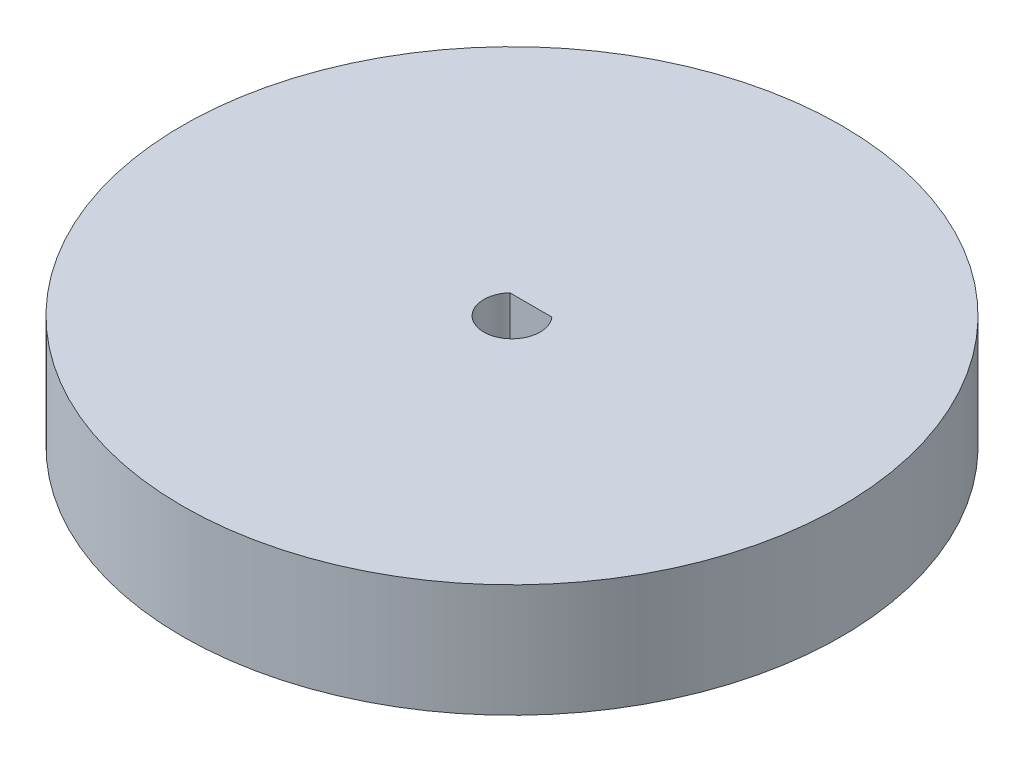
SolidWorks part; units mm, degrees
material "6063-T4"
ref_plane "Front Plane" through (0, 0, 0) normal (0, 0, 1) x (1, 0, 0)
ref_plane "Top Plane" through (0, 0, 0) normal (0, 1, 0) x (1, 0, 0)
ref_plane "Right Plane" through (0, 0, 0) normal (1, 0, 0) x (0, 0, -1)
sketch "Sketch1" plane through (0, 0, 0) normal (0, 1, 0) x (1, 0, 0)
  line L0 (0, 0) -> (0, -1.5)
  line L1 (-1.118, 1) -> (1.118, 1)
  line L2 (-1.5, 0) -> (1.5, 0)
  arc A1 (-1.118, 1) -> (1.118, 1) centre (0, 0) ccw
  circle A5 centre (0, 0) radius 17.5
  dimension "D1" = 35
  dimension "D2" = 3
  dimension "D3" = 2.5
extrude "Boss-Extrude1" add sketch "Sketch1" along normal blind 6
sketch "Sketch3" plane through (0, 6, 0) normal (0, 1, 0) x (1, 0, 0)
  line L0 (0, 0) -> (0, 17.5) construction
  line L1 (0, 0) -> (-3.0388, 17.2341) construction
  line L2 (0, 0) -> (3.0388, 17.2341) construction
  line L3 (-1.997, 11.5) -> (-1.1287, 6.5)
  line L4 (1.997, 11.5) -> (1.1287, 6.5)
  circle A0 centre (0, 11.5) radius 1.997
  circle A1 centre (0, 0) radius 17.5
  circle A2 centre (0, 0) radius 17.5 construction
  circle A3 centre (0, 6.5) radius 1.1287
  dimension "D4" = 6
  dimension "D5" = 5
  dimension "D2" = 10
  dimension "D3" = 10
  dimension "D1" = 0
extrude "Cut-Extrude1" [suppressed] cut sketch "Sketch3" against normal through all contours L4 A0 L3 | A3 L4 A0 L3 | A3
pattern_circular "CirPattern1" [suppressed] count 6 over 360
